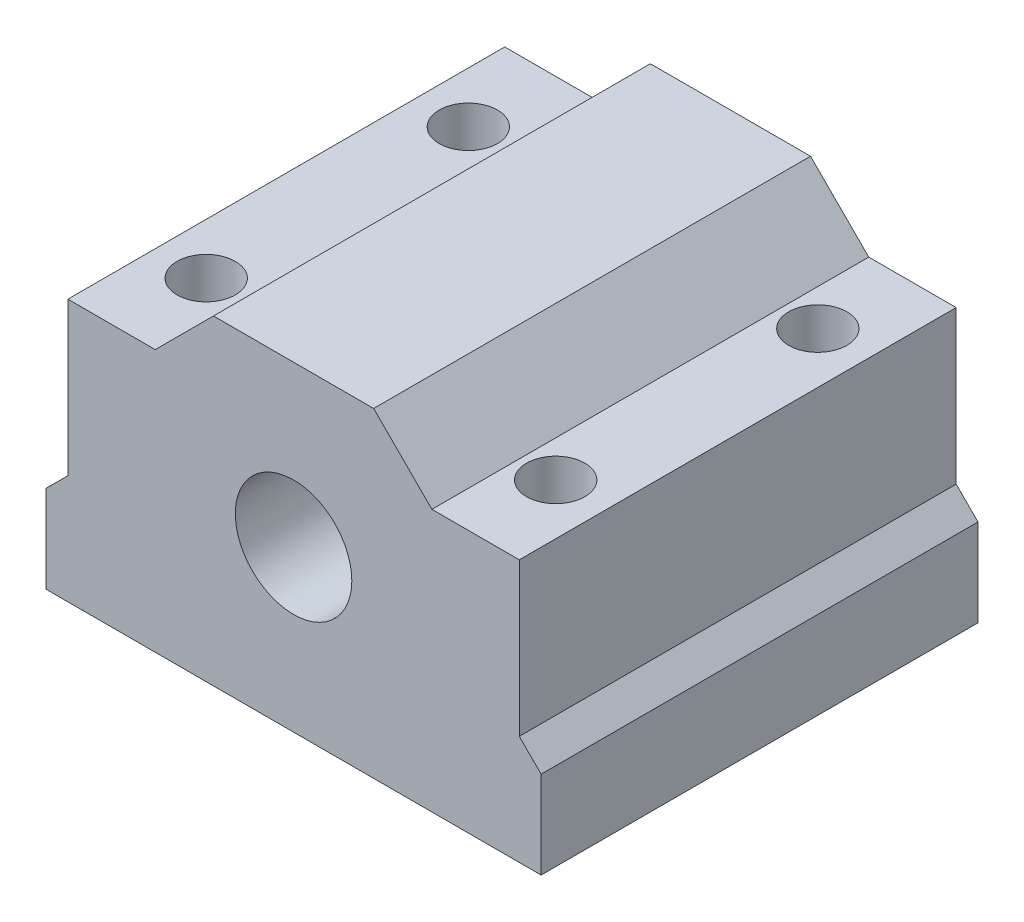
SolidWorks part; units mm, degrees
ref_plane "前视基准面" through (0, 0, 0) normal (0, 0, 1) x (1, 0, 0)
ref_plane "上视基准面" through (0, 0, 0) normal (0, 1, 0) x (1, 0, 0)
ref_plane "右视基准面" through (0, 0, 0) normal (1, 0, 0) x (0, 0, -1)
sketch "草图1" plane through (0, 0, 0) normal (0, 0, 1) x (1, 0, 0)
  line L0 (17, 0) -> (-17, 0)
  line L1 (-17, 0) -> (-17, 6)
  line L2 (-17, 6) -> (-15.5, 7.5)
  line L3 (-15.5, 7.5) -> (-15.5, 18)
  line L4 (-15.5, 18) -> (-9.5, 18)
  line L5 (-9.5, 18) -> (-5.5, 22)
  line L6 (-5.5, 22) -> (5.5, 22)
  line L7 (0, 0) -> (0, 28.1882) construction
  line L8 (9.5, 18) -> (5.5, 22)
  line L9 (15.5, 18) -> (9.5, 18)
  line L10 (15.5, 7.5) -> (15.5, 18)
  line L11 (17, 6) -> (15.5, 7.5)
  line L12 (17, 0) -> (17, 6)
  circle A0 centre (0, 11) radius 4
  point P13 (0, 22)
  dimension "D8" = 11
  dimension "D9" = 8
  dimension "D1" = 17
  dimension "D2" = 31
  dimension "D3" = 5.5
  dimension "D4" = 22
  dimension "D5" = 6
  dimension "D6" = 45
  dimension "D7" = 18
extrude "凸台-拉伸1" add sketch "草图1" along normal blind 30
sketch "草图3" plane through (0, 0, 0) normal (0, -1, 0) x (1, 0, 0)
  line L0 (0, 0) -> (0, 30) construction
  line L1 (-17, 30) -> (17, 30) construction
  line L2 (0, 15) -> (24.9782, 15) construction
  circle A0 centre (12, 24) radius 2
  circle A1 centre (-12, 24) radius 2
  circle A2 centre (-12, 6) radius 2
  circle A3 centre (12, 6) radius 2
  dimension "D1" = 18
  dimension "D3" = 4
  dimension "D2" = 24
extrude "切除-拉伸1" cut sketch "草图3" against normal through all
